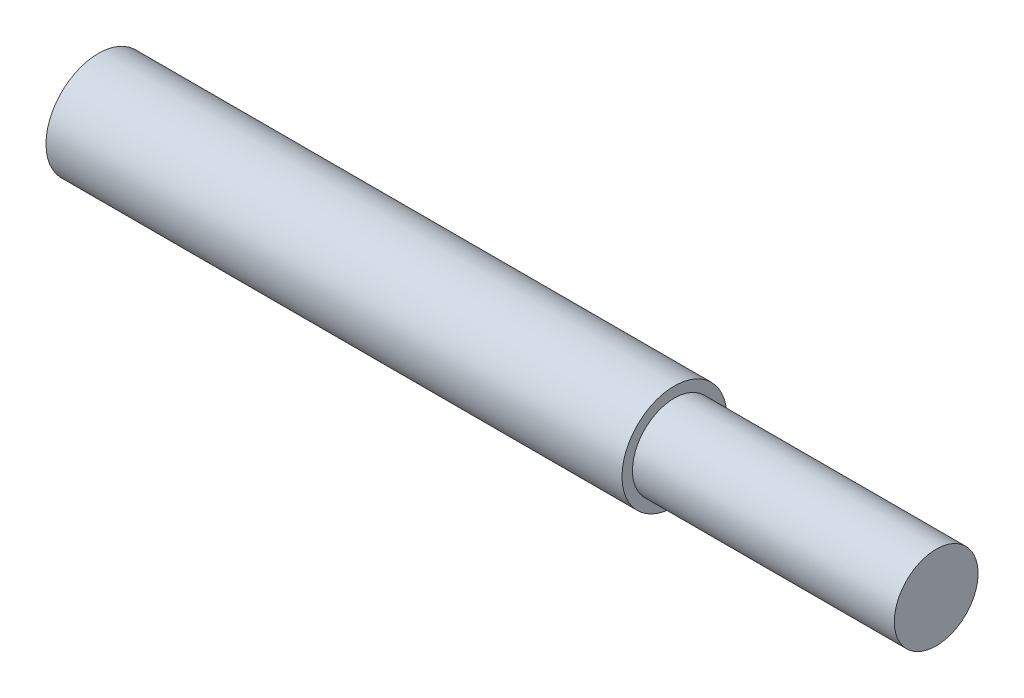
SolidWorks part; units mm, degrees
material "AISI 1020"
ref_plane "Front Plane" through (0, 0, 0) normal (0, 0, 1) x (1, 0, 0)
ref_plane "Top Plane" through (0, 0, 0) normal (0, 1, 0) x (1, 0, 0)
ref_plane "Right Plane" through (0, 0, 0) normal (1, 0, 0) x (0, 0, -1)
sketch "Sketch1" plane through (0, 0, 0) normal (0, 0, 1) x (1, 0, 0)
  line L0 (0, 0) -> (0, 4)
  line L1 (0, 4) -> (-25, 4)
  line L2 (-25, 4) -> (-25, 5)
  line L3 (-25, 5) -> (-80, 5)
  line L4 (-80, 5) -> (-80, 0)
  line L5 (-80, 0) -> (0, 0)
  dimension "D1" = 25
  dimension "D2" = 4
  dimension "D3" = 5
  dimension "D4" = 55
revolve "Revolve1" add sketch "Sketch1" angle 360 about L5
sketch "Sketch2" plane through (-80, 0, 0) normal (-1, 0, 0) x (0, 0, 1)
  line L0 (0, 0) -> (0, -5)
  circle A0 centre (0, 0) radius 5 construction
